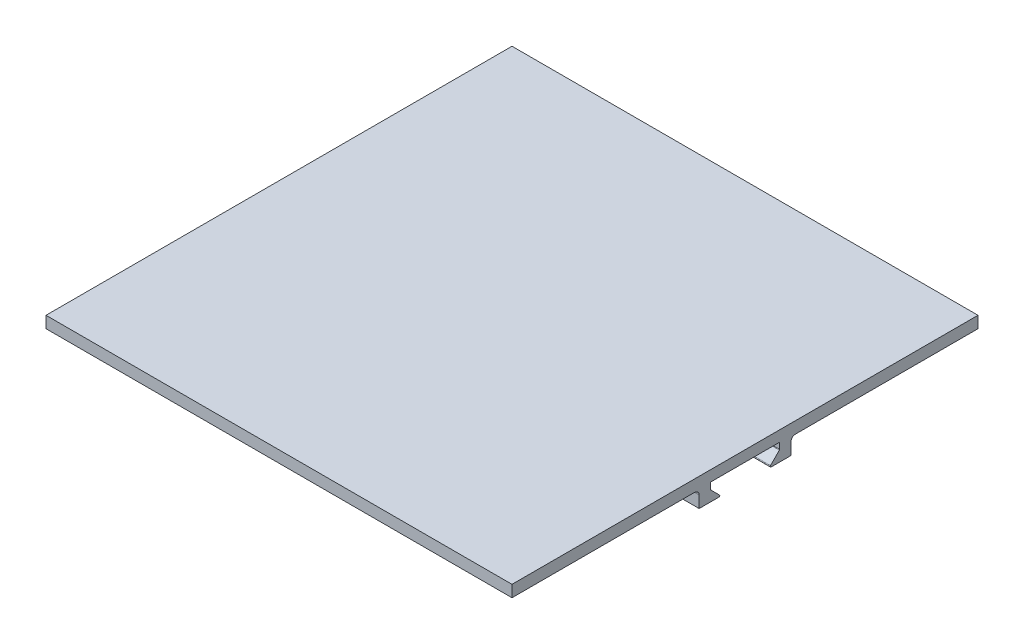
SolidWorks part; units mm, degrees
material "ABS"
ref_plane "Front Plane" through (0, 0, 0) normal (0, 0, 1) x (1, 0, 0)
ref_plane "Top Plane" through (0, 0, 0) normal (0, 1, 0) x (1, 0, 0)
ref_plane "Right Plane" through (0, 0, 0) normal (1, 0, 0) x (0, 0, -1)
sketch "Sketch1" plane through (0, 0, 0) normal (0, 1, 0) x (1, 0, 0)
  line L1 (-127, 127) -> (127, 127)
  line L2 (-127, 127) -> (-127, -127)
  line L3 (-127, -127) -> (127, -127)
  line L4 (127, 127) -> (127, -127)
  line L5 (-127, 127) -> (127, -127) construction
  line L6 (-127, -127) -> (127, 127) construction
  point P0 (0, 0)
  dimension "D1" = 254
  dimension "D2" = 254
extrude "Base" add sketch "Sketch1" along normal blind 6.35
sketch "Sketch3" plane through (0, 0, 0) normal (0, -1, 0) x (1, 0, 0)
  line L1 (-127, 25) -> (127, 25)
  line L2 (-127, 25) -> (-127, -25)
  line L3 (-127, -25) -> (127, -25)
  line L4 (127, 25) -> (127, -25)
  line L5 (-127, 25) -> (127, -25) construction
  line L6 (-127, -25) -> (127, 25) construction
  point P0 (0, 0)
  dimension "D1" = 254
  dimension "D2" = 50
extrude "Key Material" add sketch "Sketch3" along normal blind 8.89 contours L1 L4 L3 L2
sketch "Sketch10" plane through (-127, 0, 0) normal (-1, 0, 0) x (0, 0, 1)
  line L0 (-12.4912, -8.89) -> (12.5088, -8.89)
  line L1 (12.5088, -8.89) -> (12.5257, -8.7527)
  line L2 (-18.4912, 0.11) -> (-18.4912, -2.89) construction
  line L3 (-18.4912, -2.89) -> (-12.4912, -8.89) construction
  line L4 (25, -8.89) -> (-25, -8.89) construction
  line L5 (-127, 6.35) -> (127, 6.35) construction
  line L6 (18.5088, -2.89) -> (12.5088, -8.89) construction
  line L7 (18.5088, 0.11) -> (18.5088, -2.89) construction
  line L8 (-18.4912, 0.11) -> (18.5088, 0.11) construction
  line L9 (25, -8.89) -> (25, 0) construction
  line L10 (-25, -8.89) -> (-25, 0) construction
  line L11 (18.8898, -3.0478) -> (12.6666, -9.271)
  line L12 (18.8898, 0.491) -> (18.8898, -3.0478)
  line L13 (-18.8722, 0.491) -> (18.8898, 0.491)
  line L14 (-18.8722, 0.491) -> (-18.8722, -3.0478)
  line L15 (-18.8722, -3.0478) -> (-12.6491, -9.271)
  line L16 (-12.6491, -9.271) -> (12.6666, -9.271)
  dimension "D1" = 0
  dimension "D2" = 6.24
  dimension "D3" = 6.4912
  dimension "D4" = 6.5088
  dimension "D5" = 6
  dimension "D6" = 6
  dimension "D7" = 45
  dimension "D8" = 45
  dimension "D10" = 3.5388
  dimension "D9" = 0.381
extrude "Key Slide" cut sketch "Sketch10" against normal through all contours L15 L16 L11 L12 L13 L14
fillet "Key Contouring" radius 0.5 4 edges at (0, -3.0478, 18.8898) (0, -8.89, 13.0476) (0, -8.89, -13.0301) (0, -3.0478, -18.8722)
fillet "Fillet5" radius 2.54 2 edges
